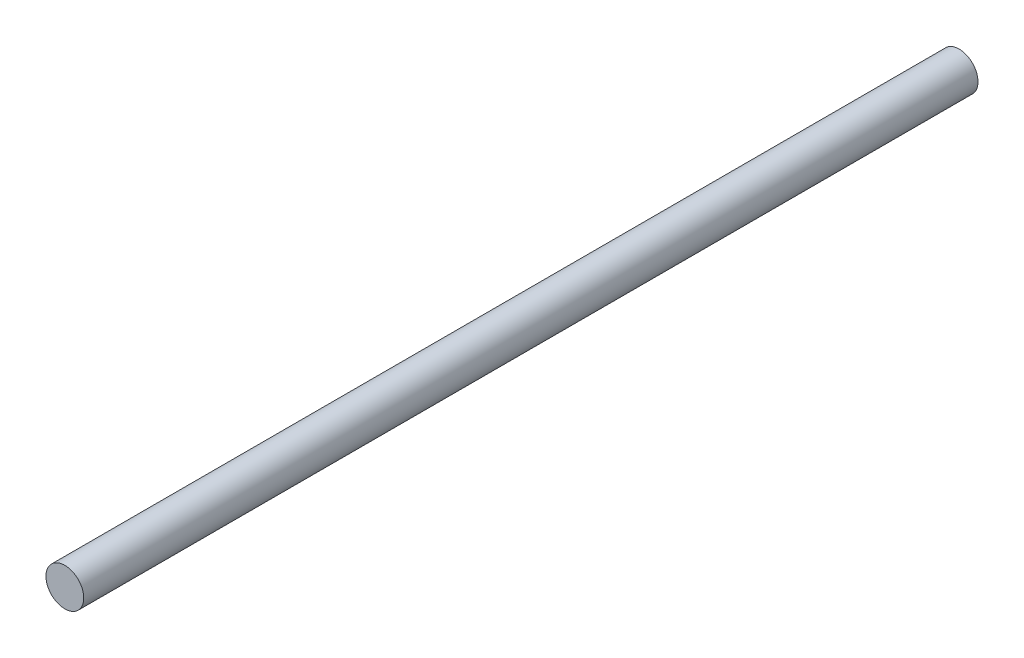
SolidWorks part; units mm, degrees
ref_plane "前视基准面" through (0, 0, 0) normal (0, 0, 1) x (1, 0, 0)
ref_plane "上视基准面" through (0, 0, 0) normal (0, 1, 0) x (1, 0, 0)
ref_plane "右视基准面" through (0, 0, 0) normal (1, 0, 0) x (0, 0, -1)
sketch "草图1" plane through (0, 0, 0) normal (0, 0, 1) x (1, 0, 0)
  circle A0 centre (0, 0) radius 3
  dimension "D1" = 6
extrude "凸台-拉伸1" add sketch "草图1" along normal blind 142
